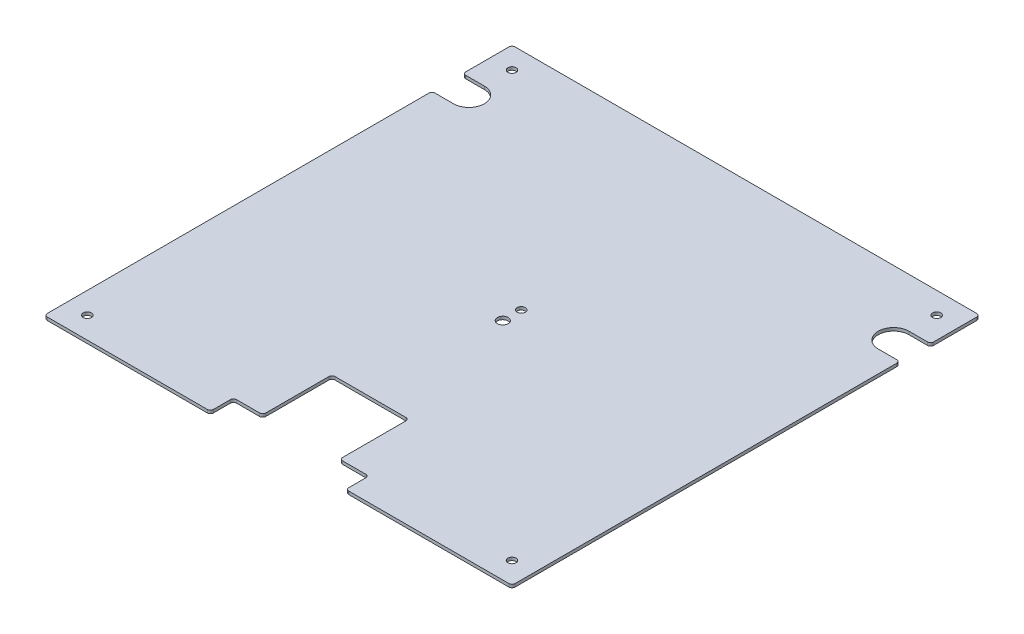
SolidWorks part; units mm, degrees
material "6061-T6 (SS)"
ref_plane "Front Plane" through (0, 0, 0) normal (0, 0, 1) x (1, 0, 0)
ref_plane "Top Plane" through (0, 0, 0) normal (0, 1, 0) x (1, 0, 0)
ref_plane "Right Plane" through (0, 0, 0) normal (1, 0, 0) x (0, 0, -1)
sketch "Sketch1" plane through (0, 0, 0) normal (0, 1, 0) x (1, 0, 0)
  line L1 (152, -152) -> (-152, -152)
  line L2 (152, -152) -> (152, 152)
  line L3 (152, 152) -> (-152, 152)
  line L4 (-152, -152) -> (-152, 152)
  line L5 (152, -152) -> (-152, 152) construction
  line L6 (152, 152) -> (-152, -152) construction
  point P0 (0, 0)
  dimension "D1" = 304
extrude "Boss-Extrude1" add sketch "Sketch1" along normal blind 2
sketch "Sketch2" plane through (0, 2, 0) normal (0, 1, 0) x (1, 0, 0)
  line L0 (-44, -152) -> (-44, -137)
  line L1 (-152, -152) -> (152, -152) construction
  line L2 (-44, -137) -> (44, -137)
  line L3 (44, -137) -> (44, -152)
  line L4 (44, -152) -> (-44, -152)
  line L5 (-152, 100) -> (-138, 100)
  line L6 (-152, 152) -> (-152, -152) construction
  line L8 (-138, 120) -> (-152, 120)
  line L9 (-152, 120) -> (-152, 100)
  line L10 (-152, 110) -> (-138, 110) construction
  line L11 (0, -152) -> (0, 152) construction
  line L12 (152, 152) -> (-152, 152) construction
  line L13 (152, 100) -> (138, 100)
  line L14 (152, 120) -> (152, 100)
  line L15 (138, 120) -> (152, 120)
  arc A0 (-138, 100) -> (-138, 120) centre (-138, 110) ccw
  arc A1 (138, 100) -> (138, 120) centre (138, 110) cw
  point P20 (0, 0)
  dimension "D1" = 108
  dimension "D2" = 196
  dimension "D3" = 15
  dimension "D4" = 20
  dimension "D5" = 262
  dimension "D6" = 14
extrude "Cut-Extrude1" cut sketch "Sketch2" against normal through all
sketch "Sketch7" plane through (0, 0, 0) normal (0, -1, 0) x (1, 0, 0)
  line L0 (44, 137) -> (-44, 137) construction
  line L1 (25, 92) -> (-25, 92)
  line L2 (25, 92) -> (25, 137)
  line L3 (25, 137) -> (-25, 137)
  line L4 (-25, 92) -> (-25, 137)
  line L5 (25, 92) -> (-25, 137) construction
  line L6 (25, 137) -> (-25, 92) construction
  line L8 (152, 122) -> (-152, 122) construction
  line L12 (-152, -100) -> (-152, 152) construction
  line L13 (152, 152) -> (152, -100) construction
  line L14 (44, 152) -> (152, 152) construction
  point P0 (0, 114.5)
  point P7 (-152, 123.4002)
  point P13 (152, 122.591)
  dimension "D1" = 50
  dimension "D2" = 30
  dimension "D3" = 30
extrude "Cut-Extrude2" cut sketch "Sketch7" against normal up to surface (2 mm away) up to face at (0, 2, -18.875)
fillet "Fillet1" radius 2 16 edges at (-44, 1, 152) (-152, 1, 152) (-152, 1, -100) (-152, 1, -120) (152, 1, -152) (152, 1, -120) (152, 1, -100) (152, 1, 152) (44, 1, 152) (44, 1, 137) (-44, 1, 137) (-152, 1, -152) (25, 1, 92) (-25, 1, 92) (25, 1, 137) (-25, 1, 137)
hole_wizard "Ø7.0 (7) Diameter Hole1" positions "Sketch3" profile "Sketch4" hole size "Ø7.0" standard "ANSI Metric" end condition up to next
sketch "Sketch3" plane through (0, 2, 0) normal (0, 1, 0) x (1, 0, 0)
  line L1 (-138, -138) -> (138, -138)
  line L2 (-138, -138) -> (-138, 138)
  line L3 (-138, 138) -> (138, 138)
  line L4 (138, -138) -> (138, 138)
  line L5 (-152, 98) -> (-152, -150) construction
  line L6 (-150, -152) -> (-46, -152) construction
  line L7 (0, 6) -> (0, -6) construction
  point P138 (0, -6)
  point P151 (0, 0)
  dimension "D1" = 14
  dimension "D2" = 14
  dimension "D3" = 290
  dimension "D4" = 290
  dimension "D5" = 152
  dimension "D6" = 146
  dimension "D7" = 158
sketch "Sketch4" plane through (0, 2, 6) normal (1, 0, 0) x (0, 0, 1)
  line L0 (0, 0) -> (0, 2)
  line L1 (0, 2) -> (3.5, 2)
  line L2 (3.5, 2) -> (3.5, 0)
  line L5 (3.5, 0) -> (0, 0)
  line L11 (0, -6.35) -> (0, 107.95) construction
  dimension "Thru Hole Dia." = 7
  dimension "Thru Hole Depth" = 2
hole_wizard "M5 Clearance Hole1" positions "Sketch5" profile "Sketch6" hole size "M5" standard "ANSI Metric" end condition up to next
sketch "Sketch5" plane through (0, 2, 0) normal (0, 1, 0) x (1, 0, 0)
  point P0 (-138, 138)
  point P3 (138, 138)
  point P6 (138, -138)
  point P9 (-138, -138)
  point P13 (0, 6)
sketch "Sketch6" plane through (-138, 2, -138) normal (1, 0, 0) x (0, 0, 1)
  line L0 (0, 0) -> (0, 2)
  line L1 (0, 2) -> (2.65, 2)
  line L2 (2.65, 2) -> (2.65, 0)
  line L5 (2.65, 0) -> (0, 0)
  line L11 (0, -6.35) -> (0, 107.95) construction
  dimension "Thru Hole Dia." = 5.3
  dimension "Thru Hole Depth" = 2
